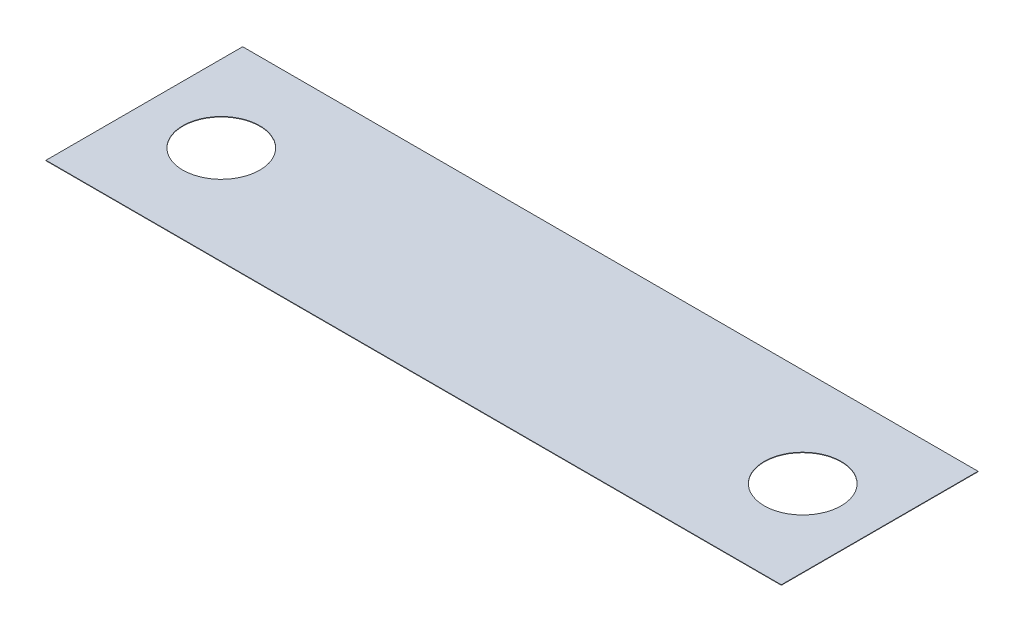
SolidWorks part; units mm, degrees
material "Low Carbon Cold Rolled"
ref_plane "Front Plane" through (0, 0, 0) normal (0, 0, 1) x (1, 0, 0)
ref_plane "Top Plane" through (0, 0, 0) normal (0, 1, 0) x (1, 0, 0)
ref_plane "Right Plane" through (0, 0, 0) normal (1, 0, 0) x (0, 0, -1)
sketch "Sketch1" plane through (0, 0, 0) normal (0, 1, 0) x (1, 0, 0)
  line L1 (0, 0) -> (86, 0)
  line L2 (0, 0) -> (0, 23)
  line L3 (0, 23) -> (86, 23)
  line L4 (86, 0) -> (86, 23)
  dimension "D1" = 86
  dimension "D2" = 23
extrude "Extrude1" add sketch "Sketch1" along normal blind 0.0508
hole_wizard "Ø9.0 (9) Diameter Hole1" positions "Sketch3" profile "Sketch4" hole size "Ø9.0" standard "Ansi Metric" end condition through all
sketch "Sketch3" plane through (0, 0.0508, 0) normal (0, 1, 0) x (-1, 0, 0)
  line L0 (-9, -11.5) -> (0, -11.5) construction
  line L1 (0, -23) -> (0, 0) construction
  line L3 (-77, -11.5) -> (-9, -11.5) construction
  line L5 (-43, -11.5) -> (-43, -23) construction
  line L6 (-86, -23) -> (0, -23) construction
  point P0 (-9, -11.5)
  point P1 (-77, -11.5)
  dimension "D1" = 68
sketch "Sketch4" plane through (9, 0.0508, -11.5) normal (1, 0, 0) x (0, 0, 1)
  line L0 (0, 0) -> (0, 0.0508)
  line L1 (0, 0.0508) -> (4.5, 0.0508)
  line L2 (4.5, 0.0508) -> (4.5, 0)
  line L5 (4.5, 0) -> (0, 0)
  line L11 (0, -6.35) -> (0, 107.95) construction
  dimension "Thru Hole Dia." = 9
  dimension "Thru Hole Depth" = 0.0508
